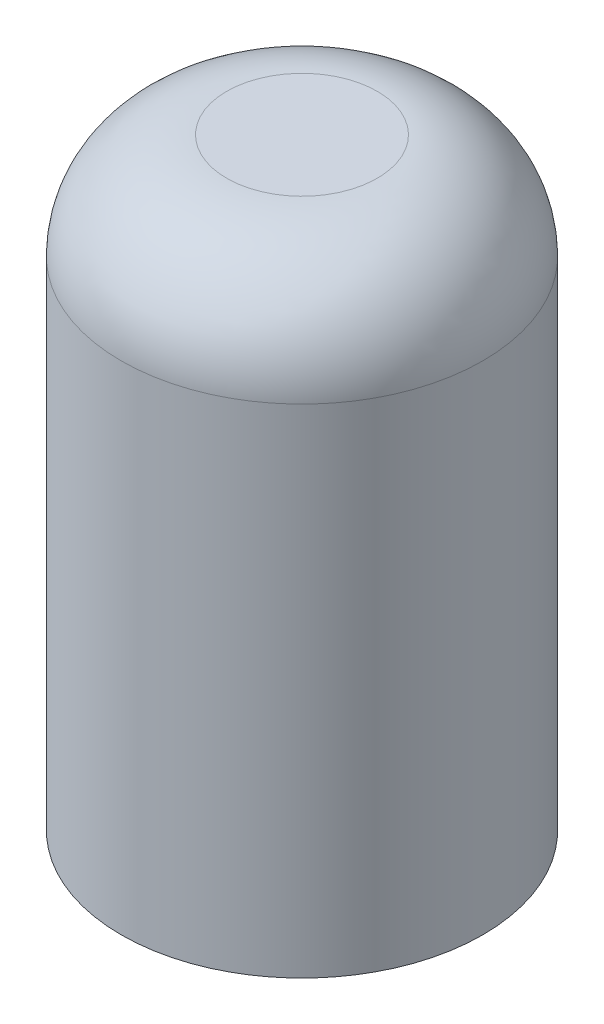
SolidWorks part; units mm, degrees
ref_plane "Front Plane" through (0, 0, 0) normal (0, 0, 1) x (1, 0, 0)
ref_plane "Top Plane" through (0, 0, 0) normal (0, 1, 0) x (1, 0, 0)
ref_plane "Right Plane" through (0, 0, 0) normal (1, 0, 0) x (0, 0, -1)
sketch "Sketch1" plane through (0, 0, 0) normal (0, 0, 1) x (1, 0, 0)
  line L0 (0, 0) -> (60, 0)
  line L1 (60, 0) -> (60, 165)
  line L2 (25, 200) -> (0, 200)
  line L3 (0, 200) -> (0, 0)
  arc A0 (60, 165) -> (25, 200) centre (25, 165) ccw
  dimension "D1" = 200
  dimension "D2" = 60
  dimension "D3" = 165
revolve "Revolve4" add sketch "Sketch1" angle 360 about L3
shell "Shell4" thickness 2
